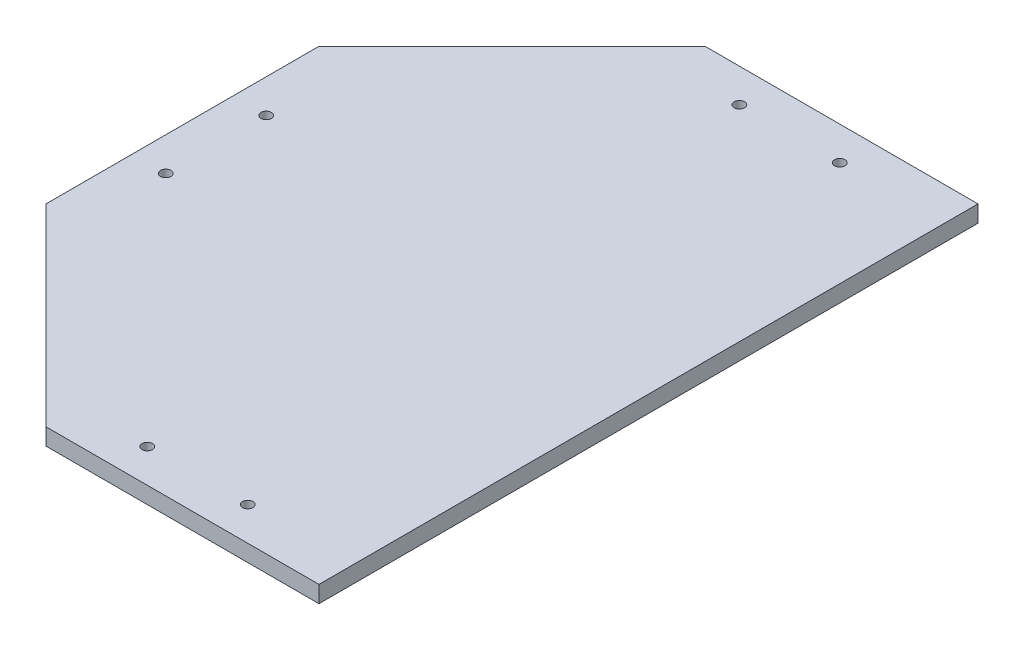
SolidWorks part; units mm, degrees
ref_plane "Front Plane" through (0, 0, 0) normal (0, 0, 1) x (1, 0, 0)
ref_plane "Top Plane" through (0, 0, 0) normal (0, 1, 0) x (1, 0, 0)
ref_plane "Right Plane" through (0, 0, 0) normal (1, 0, 0) x (0, 0, -1)
sketch "Sketch1" plane through (0, 0, 0) normal (0, 1, 0) x (1, 0, 0)
  line L8 (-125, 0) -> (125, 0) construction
  line L9 (125, 51.7767) -> (51.7767, 125)
  line L10 (51.7767, 125) -> (-51.7767, 125)
  line L11 (-51.7767, 125) -> (-125, 51.7767)
  line L12 (-125, 51.7767) -> (-125, -51.7767)
  line L13 (-125, -51.7767) -> (-51.7767, -125)
  line L14 (-51.7767, -125) -> (51.7767, -125)
  line L15 (51.7767, -125) -> (125, -51.7767)
  line L16 (125, -51.7767) -> (125, 51.7767)
  line L17 (0, 125) -> (0, -125) construction
  circle A2 centre (0, 0) radius 125 construction
  dimension "D1" = 250
extrude "Boss-Extrude1" add sketch "Sketch1" along normal blind 6.35
sketch "Sketch2" plane through (0, 6.35, 0) normal (0, 1, 0) x (1, 0, 0)
  line L0 (0, 125) -> (0, -125) construction
  line L2 (-51.7767, -125) -> (51.7767, -125) construction
  line L4 (0, 0) -> (-125, 0) construction
  line L6 (-125, 51.7767) -> (-125, -51.7767) construction
  line L7 (51.7767, 125) -> (-51.7767, 125) construction
  circle A0 centre (-26.05, -112.3) radius 1.995
  circle A5 centre (12.05, -112.3) radius 1.995
  circle A8 centre (12.05, 112.3) radius 1.995
  circle A9 centre (-26.05, 112.3) radius 1.995
  dimension "D2" = 38.1
  dimension "D1" = 3.99
  dimension "D3" = 12.7
  dimension "D4" = 26.05
extrude "Cut-Extrude1" cut sketch "Sketch2" against normal through all
sketch "Sketch5" plane through (0, 6.35, 0) normal (0, 1, 0) x (1, 0, 0)
  line L0 (-125, 51.7767) -> (-125, -51.7767) construction
  line L1 (0, 0) -> (-125, 0) construction
  circle A0 centre (-112.3, 19.05) radius 1.995
  circle A1 centre (-112.3, -19.05) radius 1.995
  point P6 (0, 0)
  dimension "D1" = 3.99
  dimension "D2" = 12.7
  dimension "D3" = 38.1
  dimension "D4" = 19.05
extrude "Cut-Extrude5" cut sketch "Sketch5" against normal through all
sketch "Sketch6" plane through (0, 6.35, 0) normal (0, 1, 0) x (1, 0, 0)
  line L4 (51.7767, -125) -> (125, -51.7767)
  line L5 (125, -51.7767) -> (125, 51.7767)
  line L6 (125, 51.7767) -> (51.7767, 125)
  line L9 (51.7767, 125) -> (51.7767, -125)
extrude "Cut-Extrude6" cut sketch "Sketch6" against normal blind 10
